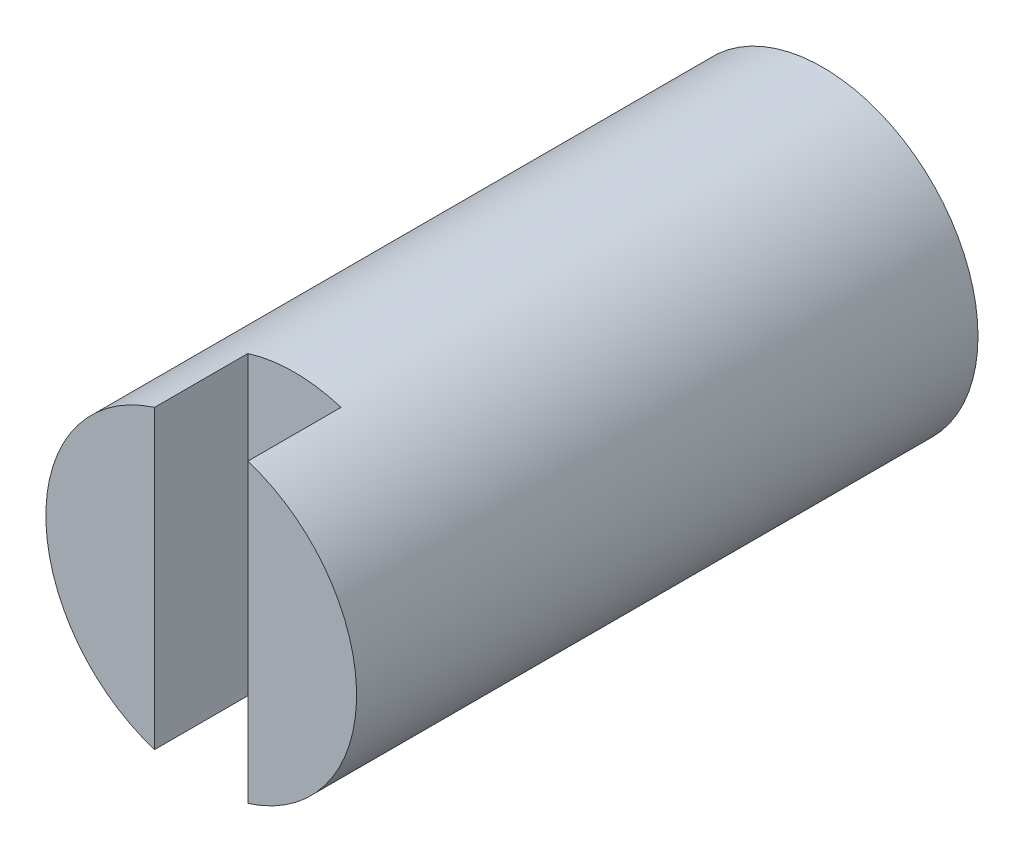
SolidWorks part; units mm, degrees
ref_plane "前视基准面" through (0, 0, 0) normal (0, 0, 1) x (1, 0, 0)
ref_plane "上视基准面" through (0, 0, 0) normal (0, 1, 0) x (1, 0, 0)
ref_plane "右视基准面" through (0, 0, 0) normal (1, 0, 0) x (0, 0, -1)
sketch "草图1" plane through (0, 0, 0) normal (0, 0, 1) x (1, 0, 0)
  circle A0 centre (0, 0) radius 2
  dimension "D1" = 4
extrude "拉伸1" add sketch "草图1" along normal blind 8
sketch "草图2" plane through (0, 0, 8) normal (0, 0, 1) x (1, 0, 0)
  line L1 (-0.6, 2.1053) -> (0.6, 2.1053)
  line L2 (-0.6, 2.1053) -> (-0.6, -2.209)
  line L3 (-0.6, -2.209) -> (0.6, -2.209)
  line L4 (0.6, 2.1053) -> (0.6, -2.209)
  dimension "D1" = 0.6
  dimension "D2" = 1.2
extrude "切除-拉伸1" cut sketch "草图2" against normal blind 1.2
